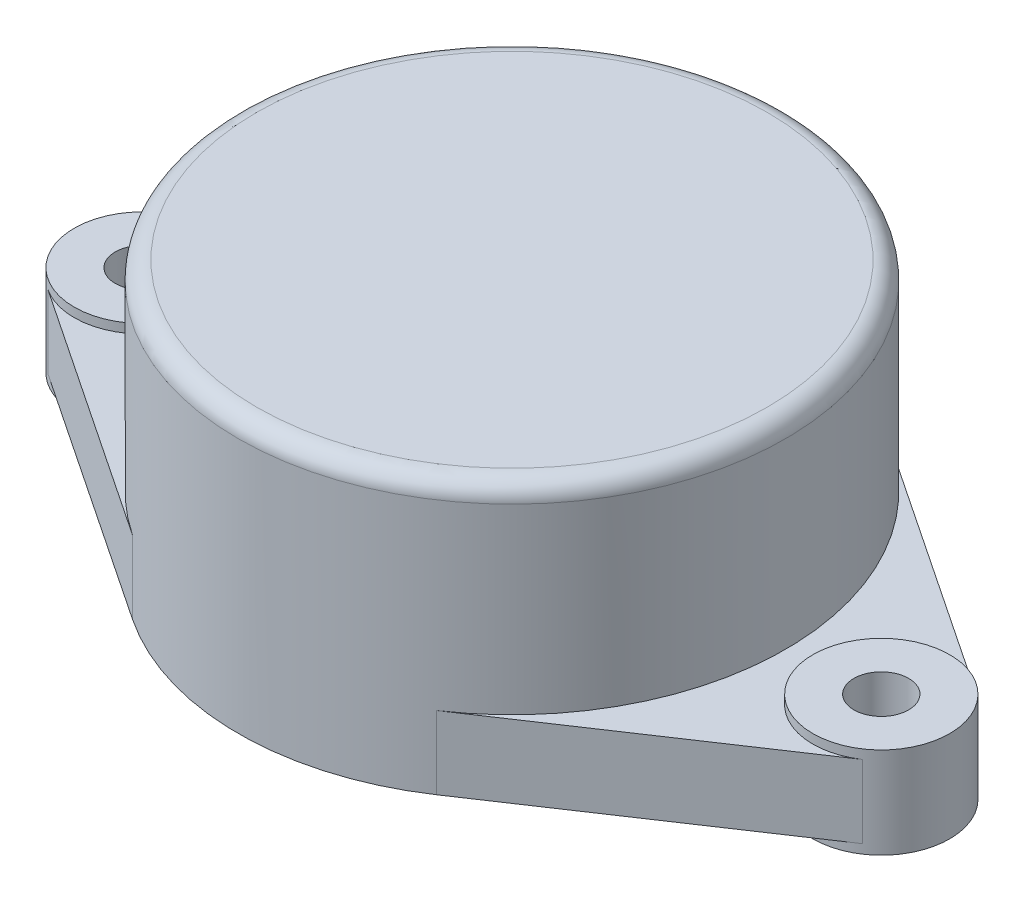
SolidWorks part; units mm, degrees
ref_plane "Front Plane" through (0, 0, 0) normal (0, 0, 1) x (1, 0, 0)
ref_plane "Top Plane" through (0, 0, 0) normal (0, 1, 0) x (1, 0, 0)
ref_plane "Right Plane" through (0, 0, 0) normal (1, 0, 0) x (0, 0, -1)
sketch "Sketch1" plane through (0, 0, 0) normal (0, 1, 0) x (1, 0, 0)
  circle A0 centre (0, 0) radius 15
  dimension "D1" = 30
extrude "Boss-Extrude1" add sketch "Sketch1" along normal blind 15
sketch "Sketch2" plane through (0, 0, 0) normal (0, 1, 0) x (1, 0, 0)
  line L0 (-37.3979, 0) -> (38.173, 0) construction
  line L1 (-22.3333, 3.118) -> (-8.3333, 12.4722)
  line L2 (-22.3333, -3.118) -> (-8.3333, -12.4722)
  line L3 (8.3333, 12.4722) -> (22.3333, 3.118)
  line L4 (8.3333, -12.4722) -> (22.3333, -3.118)
  line L5 (0, 0) -> (0, 9.6498) construction
  circle A0 centre (-20.25, 0) radius 1.5
  circle A1 centre (20.25, 0) radius 1.5
  arc A2 (-22.3333, 3.118) -> (-22.3333, -3.118) centre (-20.25, 0) ccw
  arc A3 (22.3333, 3.118) -> (22.3333, -3.118) centre (20.25, 0) cw
  circle A4 centre (0, 0) radius 15 construction
  arc A5 (-8.3333, 12.4722) -> (-8.3333, -12.4722) centre (0, 0) ccw
  arc A6 (8.3333, 12.4722) -> (8.3333, -12.4722) centre (0, 0) cw
  point P21 (-24, 0)
  point P22 (24, 0)
  dimension "D1" = 3
  dimension "D2" = 3
  dimension "D3" = 3.75
  dimension "D4" = 3.75
  dimension "D5" = 48
extrude "Boss-Extrude2" add sketch "Sketch2" along normal blind 4 contours A5 L1 A2 L2 A0 | L3 A6 L4 A3 A1
sketch "Sketch3" plane through (0, 4, 0) normal (0, 1, 0) x (1, 0, 0)
  circle A0 centre (-20.25, 0) radius 3.75
  circle A1 centre (20.25, 0) radius 3.75
  arc A2 (-22.3333, 3.118) -> (-22.3333, -3.118) centre (-20.25, 0) ccw construction
  arc A3 (22.3333, -3.118) -> (22.3333, 3.118) centre (20.25, 0) ccw construction
  circle A4 centre (-20.25, 0) radius 1.5
  circle A5 centre (20.25, 0) radius 1.5
  circle A6 centre (20.25, 0) radius 1.5 construction
  circle A7 centre (-20.25, 0) radius 1.5 construction
extrude "Boss-Extrude3" add sketch "Sketch3" along normal blind 0.5 and the other way blind 4.5
fillet "Fillet1" radius 1 1 edges at (0, 15, 15)
